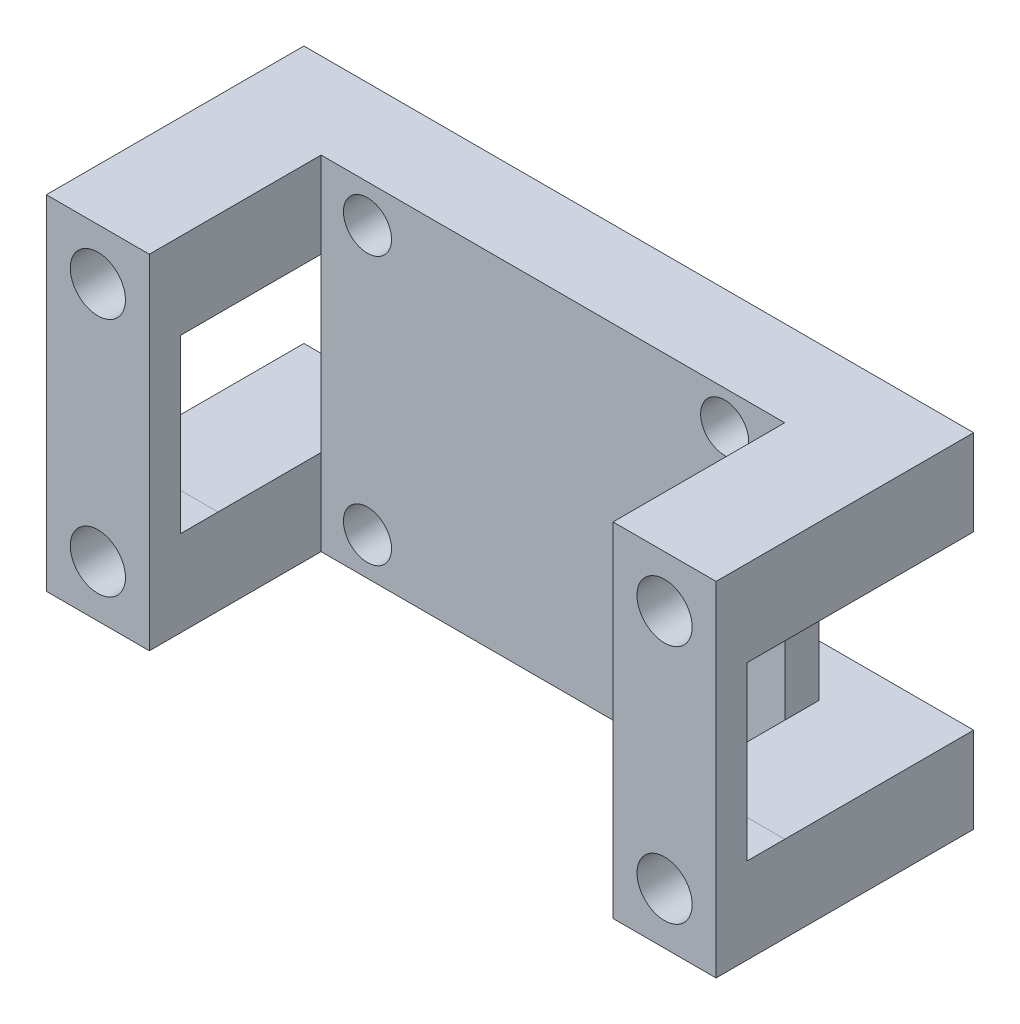
SolidWorks part; units mm, degrees
ref_plane "Front Plane" through (0, 0, 0) normal (0, 0, 1) x (1, 0, 0)
ref_plane "Top Plane" through (0, 0, 0) normal (0, 1, 0) x (1, 0, 0)
ref_plane "Right Plane" through (0, 0, 0) normal (1, 0, 0) x (0, 0, -1)
sketch "Sketch1" plane through (0, 0, 0) normal (0, 0, 1) x (1, 0, 0)
  line L1 (0, 0) -> (34.29, 0)
  line L2 (0, 0) -> (0, 25.4)
  line L3 (0, 25.4) -> (34.29, 25.4)
  line L4 (34.29, 0) -> (34.29, 25.4)
  dimension "D1" = 34.29
  dimension "D2" = 25.4
extrude "Boss-Extrude1" add sketch "Sketch1" along normal blind 2.54
sketch "Sketch3" plane through (0, 0, 0) normal (0, 0, -1) x (-1, 0, 0)
  line L0 (-34.29, 25.4) -> (0, 25.4) construction
  line L1 (7.62, 25.4) -> (-41.91, 25.4)
  line L2 (7.62, 25.4) -> (7.62, 19.05)
  line L3 (7.62, 19.05) -> (-41.91, 19.05)
  line L4 (-41.91, 25.4) -> (-41.91, 19.05)
  line L5 (7.62, 0) -> (-41.91, 0)
  line L6 (7.62, 0) -> (7.62, 6.35)
  line L7 (7.62, 6.35) -> (-41.91, 6.35)
  line L8 (-41.91, 0) -> (-41.91, 6.35)
  line L13 (0, 25.4) -> (0, 0) construction
  line L14 (-34.29, 0) -> (-34.29, 25.4) construction
  line L15 (0, 0) -> (-34.29, 0) construction
  dimension "D1" = 6.35
  dimension "D2" = 0
  dimension "D3" = 6.35
  dimension "D4" = 7.62
  dimension "D5" = 7.62
  dimension "D6" = 7.62
  dimension "D7" = 7.62
  dimension "D8" = 0
extrude "Boss-Extrude2" add sketch "Sketch3" along normal blind 3.81
sketch "Sketch2" plane through (0, 0, 2.54) normal (0, 0, 1) x (1, 0, 0)
  line L0 (34.29, 0) -> (34.29, 25.4) construction
  line L1 (0, 25.4) -> (0, 0) construction
  line L2 (34.29, 25.4) -> (0, 25.4) construction
  line L3 (0, 0) -> (34.29, 0) construction
  circle A0 centre (3.429, 22.606) radius 1.778
  circle A1 centre (29.845, 22.86) radius 1.778
  circle A2 centre (3.429, 2.794) radius 1.778
  circle A3 centre (29.845, 2.286) radius 1.778
  dimension "D1" = 3.556
  dimension "D2" = 3.556
  dimension "D3" = 3.556
  dimension "D4" = 3.556
  dimension "D5" = 4.445
  dimension "D6" = 3.429
  dimension "D7" = 3.429
  dimension "D8" = 2.794
  dimension "D9" = 2.794
  dimension "D10" = 2.286
  dimension "D11" = 2.54
  dimension "D12" = 4.445
extrude "Cut-Extrude1" cut sketch "Sketch2" against normal through all and the other way through all
sketch "Sketch5" plane through (0, 0, 0) normal (0, 0, 1) x (1, 0, 0)
  line L1 (0, 25.4) -> (-7.62, 25.4)
  line L2 (0, 25.4) -> (0, 19.05)
  line L3 (0, 19.05) -> (-7.62, 19.05)
  line L4 (-7.62, 25.4) -> (-7.62, 19.05)
  line L5 (34.29, 25.4) -> (41.91, 25.4)
  line L6 (34.29, 25.4) -> (34.29, 19.05)
  line L7 (34.29, 19.05) -> (41.91, 19.05)
  line L8 (41.91, 25.4) -> (41.91, 19.05)
  line L9 (41.91, 6.35) -> (34.29, 6.35)
  line L10 (41.91, 6.35) -> (41.91, 0)
  line L11 (41.91, 0) -> (34.29, 0)
  line L12 (34.29, 6.35) -> (34.29, 0)
  line L13 (0, 6.35) -> (-7.62, 6.35)
  line L14 (0, 6.35) -> (0, 0)
  line L15 (0, 0) -> (-7.62, 0)
  line L16 (-7.62, 6.35) -> (-7.62, 0)
extrude "Boss-Extrude3" add sketch "Sketch5" along normal blind 15.24
sketch "Sketch6" plane through (0, 0, 0) normal (0, -1, 0) x (1, 0, 0)
  line L0 (0, 15.24) -> (0, 2.54) construction
  line L1 (-7.62, 15.24) -> (0, 15.24)
  line L2 (-7.62, 15.24) -> (-7.62, 10.16)
  line L3 (-7.62, 10.16) -> (0, 10.16)
  line L4 (0, 15.24) -> (0, 10.16)
  line L5 (41.91, -3.81) -> (41.91, 15.24) construction
  line L6 (34.29, 15.24) -> (41.91, 15.24)
  line L7 (34.29, 15.24) -> (34.29, 10.16)
  line L8 (34.29, 10.16) -> (41.91, 10.16)
  line L9 (41.91, 15.24) -> (41.91, 10.16)
  dimension "D1" = 5.08
  dimension "D2" = 5.08
extrude "Boss-Extrude4" add sketch "Sketch6" against normal through all
sketch "Sketch7" plane through (0, 0, 15.24) normal (0, 0, 1) x (1, 0, 0)
  line L0 (41.91, 25.4) -> (34.29, 25.4) construction
  line L1 (41.91, 0) -> (41.91, 25.4) construction
  line L2 (34.29, 0) -> (41.91, 0) construction
  line L3 (-7.62, 25.4) -> (-7.62, 0) construction
  line L4 (-7.62, 0) -> (0, 0) construction
  line L5 (0, 25.4) -> (-7.62, 25.4) construction
  circle A0 centre (38.1, 3.81) radius 2.04
  circle A1 centre (38.1, 21.59) radius 2.04
  circle A2 centre (-3.81, 3.81) radius 2.04
  circle A3 centre (-3.81, 21.59) radius 2.04
  dimension "D1" = 4.08
  dimension "D2" = 4.08
  dimension "D3" = 4.08
  dimension "D4" = 4.08
  dimension "D6" = 3.81
  dimension "D7" = 3.81
  dimension "D8" = 3.81
  dimension "D9" = 3.81
  dimension "D10" = 3.81
  dimension "D11" = 3.81
  dimension ".15" = 3.81
  dimension "20" = 3.81
extrude "Cut-Extrude2" cut sketch "Sketch7" against normal through all
sketch "Sketch9" plane through (-7.62, 0, 0) normal (-1, 0, 0) x (0, 0, 1)
  line L0 (15.24, 25.4) -> (15.24, 0) construction
  line L1 (10.16, 19.05) -> (12.954, 19.05)
  line L2 (10.16, 19.05) -> (10.16, 6.3503)
  line L3 (10.16, 6.3503) -> (12.954, 6.3503)
  line L4 (12.954, 19.05) -> (12.954, 6.3503)
  dimension "D1" = 2.286
extrude "Cut-Extrude3" cut sketch "Sketch9" against normal through all
